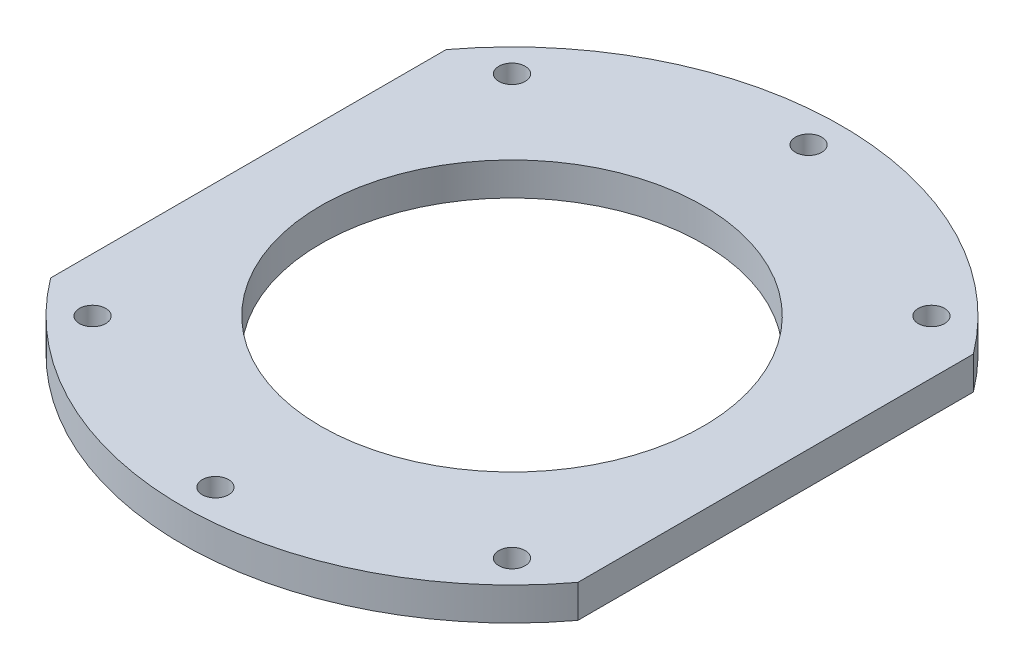
SolidWorks part; units mm, degrees
ref_plane "前视基准面" through (0, 0, 0) normal (0, 0, 1) x (1, 0, 0)
ref_plane "上视基准面" through (0, 0, 0) normal (0, 1, 0) x (1, 0, 0)
ref_plane "右视基准面" through (0, 0, 0) normal (1, 0, 0) x (0, 0, -1)
sketch "草图1" plane through (0, 0, 0) normal (0, 1, 0) x (1, 0, 0)
  circle A0 centre (0, 0) radius 29
  circle A1 centre (0, 0) radius 50
  circle A2 centre (45, 0) radius 2
  circle A3 centre (31.8198, -31.8198) radius 2
  circle A4 centre (0, -45) radius 2
  circle A5 centre (-31.8198, -31.8198) radius 2
  circle A6 centre (-45, 0) radius 2
  circle A7 centre (-31.8198, 31.8198) radius 2
  circle A8 centre (0, 45) radius 2
  circle A9 centre (31.8198, 31.8198) radius 2
  circle A10 centre (0, 0) radius 40 construction
  point P6 (50, 0)
  point P9 (40, 0)
  dimension "D1" = 58
  dimension "D2" = 80
  dimension "D3" = 5
  dimension "D4" = 4
  dimension "D6" = 5
  dimension "D5" = 8
extrude "凸台-拉伸1" add sketch "草图1" along normal blind 5
sketch "草图2" plane through (0, 5, 0) normal (0, 1, 0) x (1, 0, 0)
  line L1 (-40, -64.2431) -> (40, -64.2431)
  line L2 (-40, -64.2431) -> (-40, 64.2431)
  line L3 (-40, 64.2431) -> (40, 64.2431)
  line L4 (40, -64.2431) -> (40, 64.2431)
  line L5 (-40, -64.2431) -> (40, 64.2431) construction
  line L6 (-40, 64.2431) -> (40, -64.2431) construction
  point P0 (0, 0)
  dimension "D1" = 80
extrude "切除-拉伸-薄壁1" cut sketch "草图2" against normal blind 10 thin
